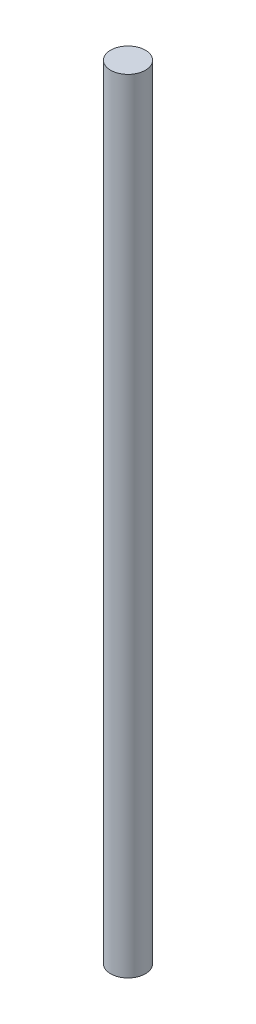
SolidWorks part; units mm, degrees
ref_plane "Front Plane" through (0, 0, 0) normal (0, 0, 1) x (1, 0, 0)
ref_plane "Top Plane" through (0, 0, 0) normal (0, 1, 0) x (1, 0, 0)
ref_plane "Right Plane" through (0, 0, 0) normal (1, 0, 0) x (0, 0, -1)
sketch "Sketch1" plane through (0, 0, 0) normal (0, 1, 0) x (1, 0, 0)
  circle A0 centre (0, 0) radius 2
  dimension "D1" = 4
extrude "Boss-Extrude1" add sketch "Sketch1" along normal blind 90
